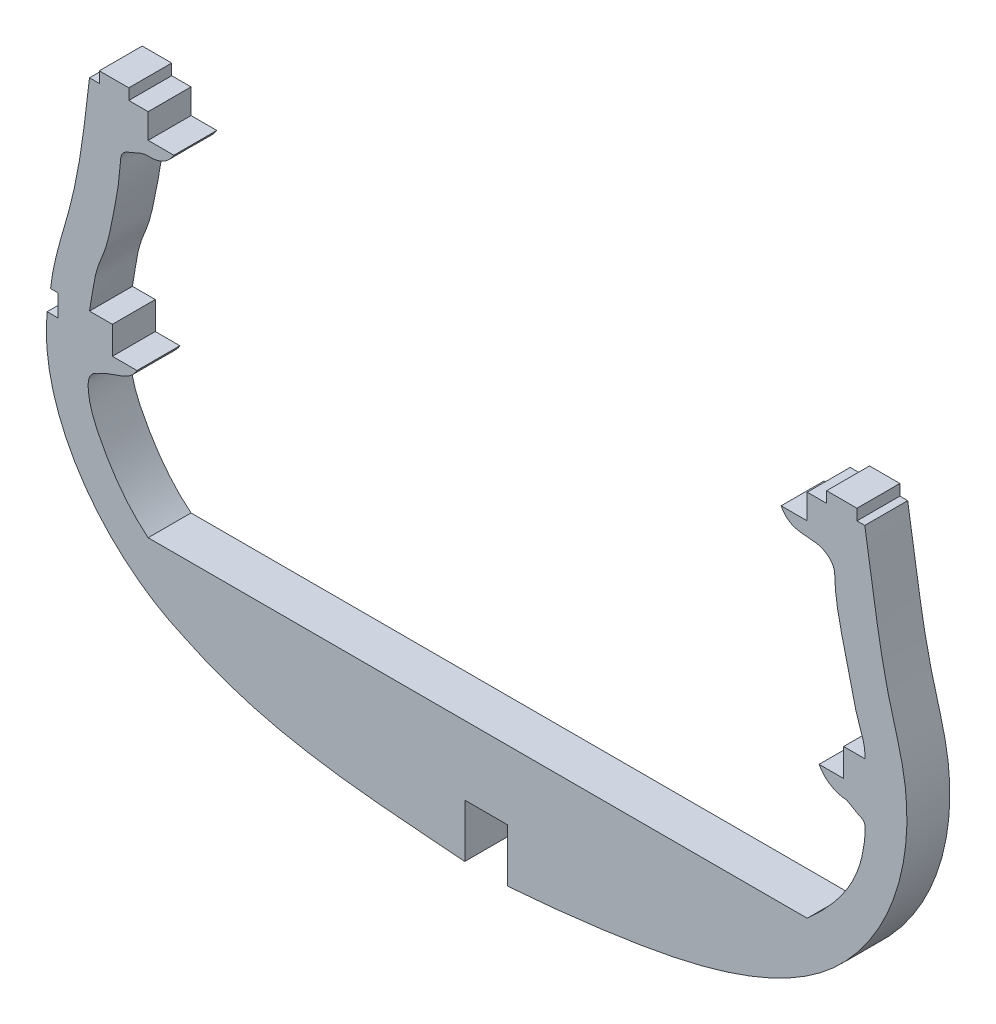
SolidWorks part; units mm, degrees
ref_plane "前视基准面" through (0, 0, 0) normal (0, 0, 1) x (1, 0, 0)
ref_plane "上视基准面" through (0, 0, 0) normal (0, 1, 0) x (1, 0, 0)
ref_plane "右视基准面" through (0, 0, 0) normal (1, 0, 0) x (0, 0, -1)
other "Configuration Table"
sketch "草图1" plane through (0, 0, 0) normal (0, 0, 1) x (1, 0, 0)
  line L0 (376.5, 617) -> (1882.5, 617) construction
  line L39 (385.358, 561.6733) -> (262.4925, 561.6733)
  line L40 (260.4105, 587.6267) -> (255.8261, 587.6267)
  line L41 (255.8261, 587.6267) -> (255.8261, 592.795)
  line L42 (255.8261, 592.795) -> (251.5635, 592.795)
  line L43 (267.2919, 625.8225) -> (262.4925, 625.8225)
  line L44 (262.4925, 625.8225) -> (262.4925, 630.4571)
  line L45 (262.4925, 630.4571) -> (258.8859, 630.4571)
  line L46 (258.8859, 630.4571) -> (258.8859, 632.5018)
  line L47 (258.8859, 632.5018) -> (253.3879, 632.5018)
  line L48 (253.3879, 632.5018) -> (253.3879, 630.4571)
  line L49 (253.3879, 630.4571) -> (251.5635, 630.4571)
  line L50 (245.7089, 588.747) -> (245.7089, 592.795)
  line L51 (245.7089, 592.795) -> (244.3004, 592.795)
  line L52 (245.7089, 588.747) -> (243.6599, 588.747)
  line L55 (321.5248, 548.8256) -> (321.5248, 538.9256)
  line L56 (396.0847, 630.4571) -> (394.6263, 630.4571)
  line L57 (394.6263, 630.4571) -> (394.6263, 632.5018)
  line L58 (394.6263, 632.5018) -> (388.9696, 632.5018)
  line L59 (388.9696, 632.5018) -> (388.9696, 630.4571)
  line L60 (388.9696, 630.4571) -> (385.358, 630.4571)
  line L61 (385.358, 630.4571) -> (385.358, 625.8225)
  line L62 (385.358, 625.8225) -> (380.4846, 625.8225)
  line L63 (396.0847, 592.795) -> (392.1433, 592.795)
  line L64 (392.1433, 592.795) -> (392.1433, 587.6267)
  line L65 (392.1433, 587.6267) -> (387.5689, 587.6267)
  line L66 (329.5237, 548.8256) -> (329.5237, 538.9256)
  line L67 (321.5248, 548.8256) -> (329.5237, 548.8256)
  spline S13 degree 3 poles (262.4925, 561.6733) (258.7552, 564.6907) (254.4892, 570.6926) (250.9586, 578.6637) (251.393, 582.912) (253.038, 583.4042) knots 0 0 0 0 0.550289 0.843333 1 1 1 1
  spline S14 degree 3 poles (253.038, 583.4042) (255.3153, 585.0874) (258.9175, 584.8262) (260.4105, 587.6267) knots 0 0 0 0 1 1 1 1
  spline S15 degree 3 poles (251.5635, 592.795) (252.0993, 595.3324) (252.3042, 599.3975) (254.8704, 604.7049) (256.0362, 611.1019) (257.2238, 616.403) (257.3508, 621.517) (260.0182, 622.5094) (261.4427, 623.4036) (262.8844, 623.278) knots 0 0 0 0 0.225137 0.340465 0.50446 0.77388 0.846142 0.887847 1 1 1 1
  spline S16 degree 2 poles (262.8844, 623.278) (265.7795, 623.3352) (267.2919, 625.8225) knots 0 0 0 1 1 1
  spline S17 degree 3 poles (251.5635, 630.4571) (250.6987, 623.1533) (249.3726, 610.3065) (244.876, 598.2301) (244.3004, 592.795) knots 0 0 0 0 0.576315 1 1 1 1
  spline S18 degree 3 poles (243.6599, 588.747) (241.9682, 572.0199) (254.0649, 555.4308) (269.2021, 548.9768) knots 0 0 0 0 1 1 1 1
  spline S19 degree 3 poles (321.5248, 538.9256) (303.815, 540.3564) (285.5377, 540.962) (269.2021, 548.9768) knots 0 0 0 0 1 1 1 1
  spline S20 degree 3 poles (329.5237, 538.9256) (336.6351, 539.4559) (350.795, 540.9843) (371.4503, 544.8943) (390.8606, 554.1499) (403.1772, 572.2525) (404.9197, 590.6396) (398.9203, 609.2583) (397.5781, 621.7283) (396.0847, 630.4571) knots 0.022563 0.022563 0.022563 0.022563 0.16962 0.313457 0.455554 0.599028 0.743616 0.817343 1 1 1 1
  spline S21 degree 3 poles (385.358, 561.6733) (390.8605, 566.6957) (395.8119, 572.3875) (396.2509, 583.2265) (395.1811, 582.7988) (392.7876, 584.4091) knots 0 0 0 0 0.778226 0.853692 1 1 1 1
  spline S22 degree 2 poles (392.7876, 584.4091) (389.209, 584.6919) (387.5689, 587.6267) knots 0 0 0 1 1 1
  spline S23 degree 3 poles (396.0847, 592.795) (396.2733, 595.0356) (394.4913, 598.6497) (392.7546, 607.7809) (390.5061, 614.5559) (390.4682, 620.0045) knots 0 0 0 0 0.233822 0.424152 1 1 1 1
  spline S24 degree 3 poles (390.4682, 620.0045) (390.3184, 621.5402) (388.2914, 623.106) (384.2668, 623.3013) (381.681, 623.5663) (380.4846, 625.8225) knots 0 0 0 0 0.359485 0.544096 1 1 1 1
  dimension "D1" = 7.9989
  dimension "D3" = 9.9
extrude "凸台-拉伸1" add sketch "草图1" along normal blind 8
